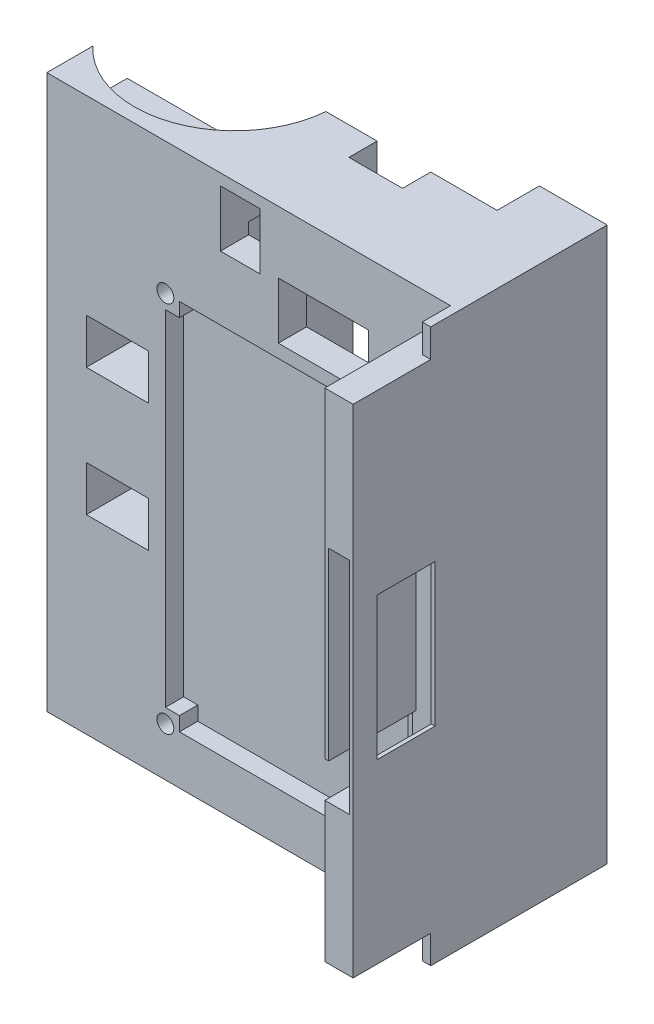
SolidWorks part; units mm, degrees
ref_plane "Front Plane" through (0, 0, 0) normal (0, 0, 1) x (1, 0, 0)
ref_plane "Top Plane" through (0, 0, 0) normal (0, 1, 0) x (1, 0, 0)
ref_plane "Right Plane" through (0, 0, 0) normal (1, 0, 0) x (0, 0, -1)
sketch "Sketch1" plane through (0, 0, 0) normal (0, 1, 0) x (1, 0, 0)
  line L1 (0, 0) -> (-72, 0)
  line L2 (0, 0) -> (0, -26.25)
  line L3 (0, -26.25) -> (-72, -26.25)
  line L4 (-72, 0) -> (-72, -26.25)
extrude "Boss-Extrude1" add sketch "Sketch1" along normal blind 98
sketch "Sketch3" plane through (0, 0, 0) normal (0, -1, 0) x (1, 0, 0)
  line L0 (0, 0) -> (-72, 0) construction
  line L1 (-72, 0) -> (-48, 0)
  line L2 (-72, 0) -> (-72, 12)
  line L3 (-72, 12) -> (-48, 12)
  line L4 (-48, 0) -> (-48, 12)
extrude "Cut-Extrude2" cut sketch "Sketch3" against normal blind 98
sketch "Sketch4" plane through (0, 0, 0) normal (0, -1, 0) x (-1, 0, 0)
  line L1 (72, -12) -> (73, -12)
  line L2 (72, -12) -> (72, -26.25)
  line L3 (72, -26.25) -> (73, -26.25)
  line L4 (73, -12) -> (73, -26.25)
extrude "Boss-Extrude2" add sketch "Sketch4" against normal blind 98
sketch "Sketch8" plane through (0, 0, 0) normal (0, -1, 0) x (1, 0, 0)
  line L0 (-73, 12) -> (-60, 12) construction
  line L1 (-48, 12) -> (-73, 12) construction
  line L2 (-60, 12) -> (-60, 6) construction
  circle A0 centre (-60, 6) radius 17.75
extrude "Cut-Extrude6" cut sketch "Sketch8" against normal blind 8
sketch "Sketch9" plane through (0, 98, 0) normal (0, 1, 0) x (1, 0, 0)
  line L0 (-73, -12) -> (-60, -12) construction
  line L1 (-48, -12) -> (-73, -12) construction
  line L2 (-60, -12) -> (-60, -6) construction
  circle A0 centre (-60, -6) radius 17.75
extrude "Cut-Extrude7" cut sketch "Sketch9" against normal blind 8
sketch "Sketch10" plane through (0, 0, 12) normal (0, 0, -1) x (-1, 0, 0)
  line L0 (73, 90) -> (73, 85) construction
  line L1 (73, 90) -> (73, 8) construction
  line L2 (73, 85) -> (69.25, 85) construction
  line L3 (69.25, 85) -> (50.75, 85) construction
  line L4 (73, 8) -> (73, 13) construction
  line L5 (73, 13) -> (69.25, 13) construction
  line L6 (69.25, 13) -> (50.75, 13) construction
  circle A0 centre (69.25, 85) radius 2.25
  circle A1 centre (50.75, 85) radius 2.25
  circle A2 centre (69.25, 13) radius 2.25
  circle A3 centre (50.75, 13) radius 2.25
extrude "Cut-Extrude8" cut sketch "Sketch10" against normal blind 4.25
sketch "Sketch11" plane through (0, 0, 0) normal (0, 0, -1) x (-1, 0, 0)
  line L0 (0, 49) -> (12, 49) construction
  line L1 (0, 98) -> (0, 0) construction
  line L2 (21.6474, 98) -> (21.6474, 88) construction
  line L3 (0, 98) -> (43.2948, 98) construction
  line L4 (0, 88) -> (12, 88) construction
  line L6 (12, 88) -> (45, 88)
  line L7 (12, 88) -> (12, 20.5)
  line L8 (12, 20.5) -> (45, 20.5)
  line L9 (45, 88) -> (45, 20.5)
extrude "Cut-Extrude9" cut sketch "Sketch11" against normal blind 21.25
sketch "Sketch12" plane through (0, 98, 0) normal (0, 1, 0) x (1, 0, 0)
  line L0 (0, 0) -> (-12, 0) construction
  line L1 (0, 0) -> (-43.2948, 0) construction
  line L2 (-12, 0) -> (-12, -7.5) construction
  line L4 (-12, -7.5) -> (-45, -7.5)
  line L5 (-12, -7.5) -> (-12, 0)
  line L6 (-12, 0) -> (-45, 0)
  line L7 (-45, -7.5) -> (-45, 0)
extrude "Cut-Extrude10" cut sketch "Sketch12" against normal blind 21.25
sketch "Sketch13" plane through (0, 98, 0) normal (0, 1, 0) x (1, 0, 0)
  line L0 (-12, -7.5) -> (-28.5, -7.5) construction
  line L1 (-42.3135, -7.5) -> (-12, -7.5) construction
  line L3 (-33.25, -2.5) -> (-23.75, -2.5)
  line L4 (-33.25, -2.5) -> (-33.25, -12.5)
  line L5 (-33.25, -12.5) -> (-23.75, -12.5)
  line L6 (-23.75, -2.5) -> (-23.75, -12.5)
  line L7 (-33.25, -2.5) -> (-23.75, -12.5) construction
  line L8 (-33.25, -12.5) -> (-23.75, -2.5) construction
extrude "Cut-Extrude11" cut sketch "Sketch13" against normal blind 21.25
sketch "Sketch14" plane through (0, 20.5, 0) normal (0, 1, 0) x (1, 0, 0)
  line L0 (-45, -7.5) -> (-39.5, -7.5) construction
  line L1 (-42.3135, -7.5) -> (-33.25, -7.5) construction
  line L2 (-39.5, -7.5) -> (-39.5, -12) construction
  line L4 (-42, -9.5) -> (-37, -9.5)
  line L5 (-42, -9.5) -> (-42, -14.5)
  line L6 (-42, -14.5) -> (-37, -14.5)
  line L7 (-37, -9.5) -> (-37, -14.5)
  line L8 (-42, -9.5) -> (-37, -14.5) construction
  line L9 (-42, -14.5) -> (-37, -9.5) construction
extrude "Cut-Extrude13" cut sketch "Sketch14" along normal blind 101.25
sketch "Sketch17" plane through (0, 0, 7.5) normal (0, 0, -1) x (-1, 0, 0)
  line L0 (45, 88) -> (39.5, 88) construction
  line L1 (45, 88) -> (33.25, 88) construction
  line L2 (39.5, 88) -> (39.5, 96) construction
  line L3 (39.5, 96) -> (35.25, 96) construction
  line L4 (35.25, 96) -> (42.25, 96) construction
  line L6 (35.25, 96) -> (42.25, 96)
  line L7 (35.25, 96) -> (35.25, 88)
  line L8 (35.25, 88) -> (42.25, 88)
  line L9 (42.25, 96) -> (42.25, 88)
extrude "Cut-Extrude14" cut sketch "Sketch17" against normal blind 7
sketch "Sketch18" plane through (0, 98, 0) normal (0, 1, 0) x (1, 0, 0)
  line L1 (-42.1798, -9.275) -> (-36.7816, -9.275)
  line L2 (-42.1798, -9.275) -> (-42.1798, -14.715)
  line L3 (-42.1798, -14.715) -> (-36.7816, -14.715)
  line L4 (-36.7816, -9.275) -> (-36.7816, -14.715)
extrude "Boss-Extrude3" add sketch "Sketch18" against normal blind 2
sketch "Sketch19" plane through (0, 0, 26.25) normal (0, 0, 1) x (1, 0, 0)
  line L0 (0, 98) -> (-16, 98) construction
  line L1 (-16, 98) -> (-16, 87) construction
  line L3 (-16, 87) -> (-32, 87)
  line L4 (-16, 87) -> (-16, 77)
  line L5 (-16, 77) -> (-32, 77)
  line L6 (-32, 87) -> (-32, 77)
extrude "Cut-Extrude15" cut sketch "Sketch19" against normal blind 12
sketch "Sketch22" plane through (0, 0, 0) normal (0, 0, -1) x (-1, 0, 0)
  line L0 (0, 49) -> (12, 49) construction
  line L1 (0, 98) -> (0, 0) construction
  line L2 (12, 98) -> (12, 20.5) construction
  line L3 (6, 49) -> (6, 55.73) construction
  line L4 (6, 49) -> (6, 42.27) construction
  circle A0 centre (6, 55.73) radius 1.5
  circle A1 centre (6, 42.27) radius 1.5
extrude "Cut-Extrude16" cut sketch "Sketch22" against normal blind 8.2
sketch "Sketch23" plane through (0, 0, 26.25) normal (0, 0, 1) x (1, 0, 0)
  line L1 (-73, 98) -> (-73, 0) construction
  line L2 (-73, 0) -> (-73, 33.7) construction
  line L3 (-73, 33.7) -> (-66, 33.7) construction
  line L4 (-73, 98) -> (-73, 64.3) construction
  line L5 (-73, 64.3) -> (-66, 64.3) construction
  line L6 (-66, 33.7) -> (-55, 33.7)
  line L7 (-66, 33.7) -> (-66, 41.7)
  line L8 (-66, 41.7) -> (-55, 41.7)
  line L9 (-55, 33.7) -> (-55, 41.7)
  line L10 (-66, 64.3) -> (-55, 64.3)
  line L11 (-66, 64.3) -> (-66, 56.3)
  line L12 (-66, 56.3) -> (-55, 56.3)
  line L13 (-55, 64.3) -> (-55, 56.3)
extrude "Cut-Extrude18" cut sketch "Sketch23" against normal through all
sketch "Sketch25" plane through (-73, 0, 0) normal (-1, 0, 0) x (0, 0, 1)
  line L0 (26.25, 49) -> (12, 49) construction
  line L1 (26.25, 98) -> (26.25, 0) construction
  line L2 (12, 90) -> (12, 8) construction
  line L3 (12, 49) -> (19.125, 49) construction
  line L4 (19.125, 49) -> (19.125, 77) construction
  line L5 (19.125, 49) -> (19.125, 21) construction
  circle A0 centre (19.125, 77) radius 2.25
  circle A1 centre (19.125, 49) radius 2.25
  circle A2 centre (19.125, 21) radius 2.25
extrude "Cut-Extrude20" cut sketch "Sketch25" against normal blind 10.25
sketch "Sketch26" plane through (0, 0, 14.5) normal (0, 0, -1) x (-1, 0, 0)
  line L0 (45, 88) -> (12, 88) construction
  line L1 (35.25, 96) -> (42.25, 96)
  line L2 (35.25, 96) -> (35.25, 88)
  line L3 (35.25, 88) -> (42.25, 88)
  line L4 (42.25, 96) -> (42.25, 88)
  line L5 (45, 88) -> (42.25, 88) construction
extrude "Cut-Extrude21" cut sketch "Sketch26" against normal through all
sketch "Sketch28" plane through (0, 0, 7.5) normal (0, 0, -1) x (-1, 0, 0)
  line L0 (45, 88) -> (42.25, 88) construction
  line L1 (35.0663, 96.136) -> (42.2663, 96.136)
  line L2 (35.0663, 96.136) -> (35.0663, 88)
  line L3 (35.0663, 88) -> (42.2663, 88)
  line L4 (42.2663, 96.136) -> (42.2663, 88)
extrude "Boss-Extrude6" add sketch "Sketch28" against normal blind 2
sketch "Sketch31" plane through (0, 0, 26.25) normal (0, 0, 1) x (1, 0, 0)
  line L0 (-6.0078, 77.6515) -> (-9.0078, 77.6515) construction
  line L1 (-55.0078, 77.6515) -> (-6.0078, 77.6515)
  line L2 (-55.0078, 77.6515) -> (-55.0078, 5.6515)
  line L3 (-55.0078, 5.6515) -> (-6.0078, 5.6515)
  line L4 (-6.0078, 77.6515) -> (-6.0078, 5.6515)
  line L5 (-9.0078, 77.6515) -> (-9.0078, 74.6515) construction
  line L6 (-55.0078, 77.6515) -> (-52.0078, 77.6515) construction
  line L7 (-52.0078, 77.6515) -> (-52.0078, 74.6515) construction
  line L8 (-52.0078, 74.6515) -> (-52.0078, 8.6257) construction
  line L9 (-52.0078, 8.6257) -> (-9.0078, 8.6257) construction
  circle A0 centre (-52.0078, 74.6515) radius 1.5
  circle A1 centre (-9.0078, 74.6515) radius 1.5
  circle A2 centre (-9.0078, 8.6257) radius 1.5
  circle A3 centre (-52.0078, 8.6257) radius 1.5
extrude "Cut-Extrude24" cut sketch "Sketch31" against normal blind 3.25 contours A0 | A1 | A2 | A3
sketch "Sketch32" plane through (0, 0, 26.25) normal (0, 0, 1) x (1, 0, 0)
  line L1 (0, 98) -> (-5, 98)
  line L2 (0, 98) -> (0, 0)
  line L3 (0, 0) -> (-5, 0)
  line L4 (-5, 98) -> (-5, 0)
extrude "Boss-Extrude7" add sketch "Sketch32" along normal blind 18.75
sketch "Sketch34" plane through (0, 0, 45) normal (0, 0, 1) x (1, 0, 0)
  line L1 (0, 98) -> (-5, 98)
  line L2 (0, 98) -> (0, 93)
  line L3 (0, 93) -> (-5, 93)
  line L4 (-5, 98) -> (-5, 93)
  line L5 (0, 0) -> (-5, 0)
  line L6 (0, 0) -> (0, 5)
  line L7 (0, 5) -> (-5, 5)
  line L8 (-5, 0) -> (-5, 5)
extrude "Cut-Extrude27" cut sketch "Sketch34" against normal blind 13.75
sketch "Sketch35" plane through (0, 0, 31.25) normal (0, 0, 1) x (1, 0, 0)
  line L1 (-5, 98) -> (-1.5, 98)
  line L2 (-5, 98) -> (-5, 93)
  line L3 (-5, 93) -> (-1.5, 93)
  line L4 (-1.5, 98) -> (-1.5, 93)
  line L5 (-5, 5) -> (-1.5, 5)
  line L6 (-5, 5) -> (-5, 0)
  line L7 (-5, 0) -> (-1.5, 0)
  line L8 (-1.5, 5) -> (-1.5, 0)
extrude "Cut-Extrude28" cut sketch "Sketch35" against normal blind 5
sketch "Sketch36" plane through (0, 0, 45) normal (0, 0, 1) x (1, 0, 0)
  line L0 (0, 93) -> (0, 5) construction
  line L1 (0, 49.25) -> (-2.5, 49.25) construction
  line L2 (-2.5, 49.25) -> (-0.8, 49.25) construction
  line L7 (-2.5, 49.25) -> (-4.325, 49.25) construction
  line L8 (-4.325, 49.25) -> (-4.325, 68.75) construction
  line L15 (-4.325, 68.75) -> (-0.675, 68.75)
  line L16 (-4.325, 68.75) -> (-4.325, 29.75)
  line L17 (-4.325, 29.75) -> (-0.675, 29.75)
  line L18 (-0.675, 68.75) -> (-0.675, 29.75)
sketch "Sketch37" plane through (0, 0, 0) normal (1, 0, 0) x (0, 0, -1)
  line L0 (-45, 49) -> (-35.625, 49) construction
  line L7 (-35.625, 49) -> (-30.5, 49) construction
  line L8 (-30.5, 49) -> (-30.5, 36.375) construction
  line L10 (-30.5, 36.375) -> (-40.75, 36.375)
  line L11 (-30.5, 36.375) -> (-30.5, 61.625)
  line L12 (-30.5, 61.625) -> (-40.75, 61.625)
  line L13 (-40.75, 36.375) -> (-40.75, 61.625)
extrude "Cut-Extrude29" cut sketch "Sketch37" against normal blind 3
extrude "Cut-Extrude30" cut sketch "Sketch36" against normal blind 15.5
sketch "Sketch38" plane through (0, 0, 45) normal (0, 0, 1) x (1, 0, 0)
  line L0 (-4.325, 30.125) -> (-4.325, 29.75)
  line L10 (-4.325, 30.125) -> (-4.325, 36.125)
  line L11 (-4.325, 36.125) -> (-5.005, 36.125)
  line L12 (-5.005, 30.125) -> (-5.005, 36.125)
  line L13 (-4.325, 29.75) -> (-5, 29.75)
  line L14 (-5, 29.75) -> (-5.005, 30.125)
extrude "Cut-Extrude31" cut sketch "Sketch38" against normal blind 15.5
sketch "Sketch39" plane through (0, 0, 26.25) normal (0, 0, 1) x (1, 0, 0)
  line L0 (-9.0078, 74.6515) -> (-9.0078, 72.1515) construction
  line L1 (-9.0078, 72.1515) -> (-11.5078, 72.1515) construction
  line L2 (-11.5078, 72.1515) -> (-11.5078, 74.6515) construction
  line L3 (-52.0078, 74.6515) -> (-49.5078, 74.6515) construction
  line L4 (-52.0078, 8.6257) -> (-52.0078, 11.1257) construction
  line L5 (-52.0078, 11.1257) -> (-49.5078, 11.1257) construction
  line L18 (-49.5078, 72.1515) -> (-52.0078, 72.1515)
  line L19 (-49.5078, 72.1515) -> (-49.5078, 74.6515)
  line L20 (-49.5078, 74.6515) -> (-11.5078, 74.6515)
  line L21 (-11.5078, 74.6515) -> (-11.5078, 72.1515)
  line L22 (-11.5078, 72.1515) -> (-9.0078, 72.1515)
  line L23 (-9.0078, 72.1515) -> (-9.0078, 11.1257)
  line L24 (-9.0078, 11.1257) -> (-11.5078, 11.1257)
  line L25 (-11.5078, 11.1257) -> (-11.5078, 8.6257)
  line L26 (-11.5078, 8.6257) -> (-49.5078, 8.6257)
  line L27 (-49.5078, 8.6257) -> (-49.5078, 11.1257)
  line L28 (-49.5078, 11.1257) -> (-52.0078, 11.1257)
  line L29 (-52.0078, 11.1257) -> (-52.0078, 72.1515)
extrude "Cut-Extrude32" cut sketch "Sketch39" against normal blind 3.25
sketch "Sketch41" plane through (0, 0, 7.5) normal (0, 0, -1) x (-1, 0, 0)
  line L1 (35.25, 88) -> (42.25, 88)
  line L2 (35.25, 88) -> (35.25, 90.5)
  line L3 (35.25, 90.5) -> (42.25, 90.5)
  line L4 (42.25, 88) -> (42.25, 90.5)
extrude "Cut-Extrude33" cut sketch "Sketch41" against normal blind 3
sketch "Sketch42" plane through (0, 0, 26.25) normal (0, 0, 1) x (1, 0, 0)
  line L1 (-42.25, 88) -> (-35.25, 88)
  line L2 (-42.25, 88) -> (-42.25, 86)
  line L3 (-42.25, 86) -> (-35.25, 86)
  line L4 (-35.25, 88) -> (-35.25, 86)
extrude "Cut-Extrude34" cut sketch "Sketch42" against normal blind 6
sketch "Sketch43" plane through (0, 0, 0) normal (0, 0, -1) x (-1, 0, 0)
  line L1 (45, 90) -> (48, 90)
  line L2 (45, 90) -> (45, 79.5)
  line L3 (45, 79.5) -> (48, 79.5)
  line L4 (48, 90) -> (48, 79.5)
  line L5 (48, 8) -> (45, 8)
  line L6 (48, 8) -> (48, 18.5)
  line L7 (48, 18.5) -> (45, 18.5)
  line L8 (45, 8) -> (45, 18.5)
extrude "Cut-Extrude35" cut sketch "Sketch43" against normal blind 12
